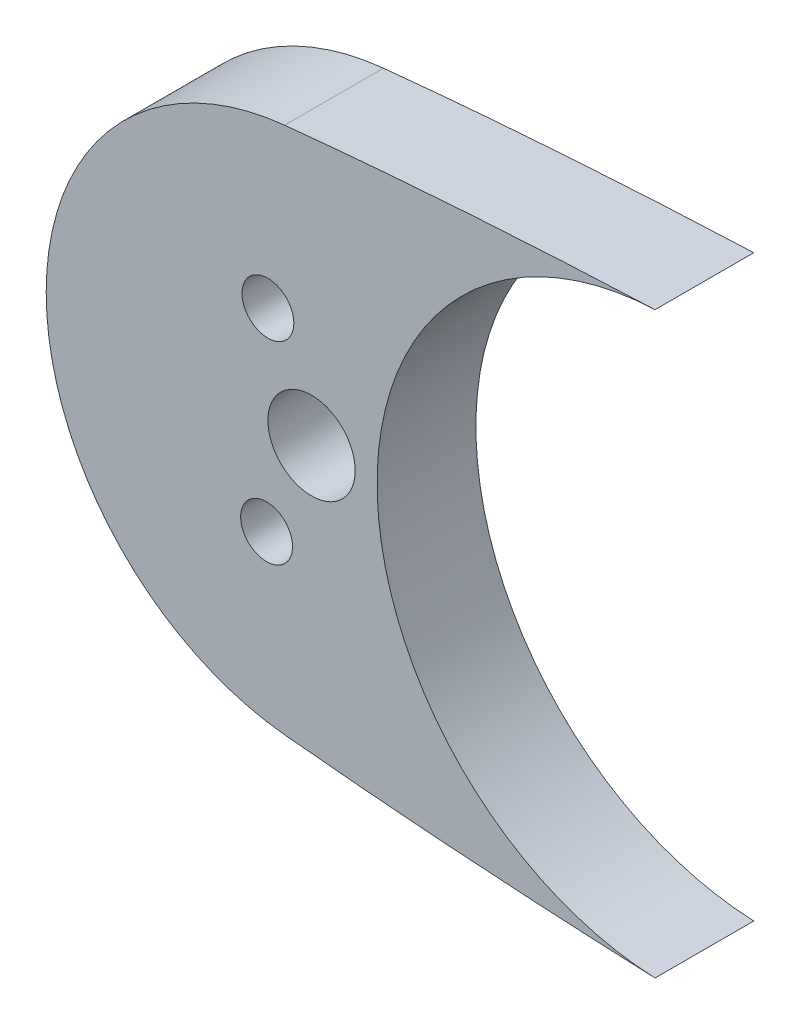
SolidWorks part; units mm, degrees
ref_plane "Front Plane" through (0, 0, 0) normal (0, 0, 1) x (1, 0, 0)
ref_plane "Top Plane" through (0, 0, 0) normal (0, 1, 0) x (1, 0, 0)
ref_plane "Right Plane" through (0, 0, 0) normal (1, 0, 0) x (0, 0, -1)
other "Center of Mass"
curve "Curve2"
  spline degree 3 poles (300, 0.378, 0) (299.8459, 0.3996, 0) (299.2303, 0.4859, 0) (297.8489, 0.6785, 0) (295.556, 0.9968, 0) (292.3657, 1.4334, 0) (288.2979, 1.9834, 0) (283.3772, 2.6357, 0) (277.6343, 3.3815, 0) (271.1045, 4.209, 0) (263.8281, 5.1072, 0) (255.8498, 6.0628, 0) (247.219, 7.0642, 0) (237.9888, 8.0979, 0) (228.216, 9.1511, 0) (217.9611, 10.2107, 0) (207.2872, 11.2632, 0) (196.2601, 12.2937, 0) (184.9478, 13.2887, 0) (173.4201, 14.2316, 0) (161.7479, 15.107, 0) (150.0032, 15.8986, 0) (138.2584, 16.5898, 0) (126.5858, 17.1634, 0) (115.0575, 17.6038, 0) (103.7442, 17.8968, 0) (92.7158, 18.028, 0) (82.0402, 17.9871, 0) (71.7831, 17.7661, 0) (62.0077, 17.3595, 0) (52.7741, 16.7661, 0) (44.1391, 15.9878, 0) (36.1555, 15.0306, 0) (28.872, 13.9026, 0) (22.3327, 12.6157, 0) (16.576, 11.1845, 0) (11.6345, 9.6228, 0) (7.5334, 7.9452, 0) (4.2857, 6.163, 0) (1.8965, 4.2728, 0) (0.3663, 2.2288, 0) (-0.1707, 0, 0) (0.3663, -2.2288, 0) (1.8965, -4.2728, 0) (4.2857, -6.163, 0) (7.5334, -7.9452, 0) (11.6345, -9.6228, 0) (16.576, -11.1845, 0) (22.3327, -12.6157, 0) (28.872, -13.9026, 0) (36.1555, -15.0306, 0) (44.1391, -15.9878, 0) (52.7741, -16.7661, 0) (62.0077, -17.3595, 0) (71.7831, -17.7661, 0) (82.0402, -17.9871, 0) (92.7158, -18.028, 0) (103.7442, -17.8968, 0) (115.0575, -17.6038, 0) (126.5858, -17.1634, 0) (138.2584, -16.5898, 0) (150.0032, -15.8986, 0) (161.7479, -15.107, 0) (173.4201, -14.2316, 0) (184.9478, -13.2887, 0) (196.2601, -12.2937, 0) (207.2872, -11.2632, 0) (217.9611, -10.2107, 0) (228.216, -9.1511, 0) (237.9888, -8.0979, 0) (247.219, -7.0642, 0) (255.8498, -6.0628, 0) (263.8281, -5.1072, 0) (271.1045, -4.209, 0) (277.6343, -3.3815, 0) (283.3772, -2.6357, 0) (288.2979, -1.9834, 0) (292.3657, -1.4334, 0) (295.556, -0.9968, 0) (297.8489, -0.6785, 0) (299.2303, -0.4859, 0) (299.8459, -0.3996, 0) (300, -0.378, 0) knots 0 0 0 0 0.000763 0.003048 0.006841 0.012116 0.018841 0.026973 0.03646 0.047243 0.059254 0.072417 0.086651 0.101866 0.117969 0.134858 0.152428 0.170572 0.189175 0.208122 0.227297 0.24658 0.265853 0.284997 0.303895 0.322433 0.340499 0.357984 0.374788 0.390812 0.405965 0.420162 0.433328 0.445394 0.456301 0.466004 0.474472 0.481696 0.487704 0.492583 0.496544 0.5 0.503456 0.507417 0.512296 0.518304 0.525528 0.533996 0.543699 0.554606 0.566672 0.579838 0.594035 0.609188 0.625212 0.642016 0.659501 0.677567 0.696105 0.715003 0.734147 0.75342 0.772703 0.791878 0.810825 0.829428 0.847572 0.865142 0.882031 0.898134 0.913349 0.927583 0.940746 0.952757 0.96354 0.973027 0.981159 0.987884 0.993159 0.996952 0.999237 1 1 1 1
sketch "Sketch2" plane through (0, 0, 0) normal (0, 0, 1) x (1, 0, 0)
  line L0 (0, 0) -> (300.3287, 0) construction
  line L9 (300, 0.378) -> (300, -0.378)
  line L17 (90, 18.0052) -> (90, -18.0052)
  line L20 (25.2817, 12.903) -> (25.2817, -12.903)
  line L21 (46.6322, 16.1183) -> (46.6322, -16.1183)
  line L22 (68.2099, 17.5933) -> (68.2099, -17.5933)
  line L23 (131.5031, 16.8963) -> (131.5031, -16.8963)
  line L24 (173.2123, 14.1909) -> (173.2123, -14.1909)
  line L25 (215.2898, -10.4186) -> (215.2898, 10.4186)
  line L26 (257.3103, -5.8439) -> (257.3103, 5.8439)
  arc A0 (300, -0.378) -> (300, 0.378) centre (299.947, 0) ccw
  arc A3 (45, 16.0354) -> (45, -16.0354) centre (46.6322, 0) ccw
  arc A5 (67.5, -17.5789) -> (67.5, 17.5789) centre (68.2099, 0) cw
  arc A6 (22.5, 12.5996) -> (22.5, -12.5996) centre (25.2817, 0) ccw
  arc A7 (258, -5.8031) -> (258, 5.8031) centre (257.3103, 0) cw
  arc A8 (216.3287, -10.3667) -> (216.3287, 10.3667) centre (215.2898, 0) cw
  arc A9 (174.3287, -14.147) -> (174.3287, 14.147) centre (173.2123, 0) cw
  arc A11 (132.3287, -16.8761) -> (132.3287, 16.8761) centre (131.5031, 0) cw
  arc A12 (90, -18.0052) -> (90, 18.0052) centre (89.9987, 0) cw
  arc A13 (22.5, 12.5996) -> (22.5, -12.5996) centre (25.2817, 0) cw
  arc A14 (45, 16.0354) -> (45, -16.0354) centre (46.6322, 0) cw
  arc A15 (67.5, 17.5789) -> (67.5, -17.5789) centre (68.2099, 0) cw
  arc A16 (90, -18.0052) -> (90, 18.0052) centre (90, 0) ccw
  arc A17 (132.3287, 16.8761) -> (132.3287, -16.8761) centre (131.5031, 0) cw
  arc A18 (174.3287, 14.147) -> (174.3287, -14.147) centre (173.2123, 0) cw
  arc A19 (216.3287, 10.3667) -> (216.3287, -10.3667) centre (215.2898, 0) cw
  arc A20 (257.9987, 5.8032) -> (257.9987, -5.8032) centre (257.309, 0) cw
  circle A21 centre (25.2817, 0) radius 12.903
  circle A22 centre (257.3103, 0) radius 5.8439
  circle A23 centre (25.2817, 0) radius 2.65
  circle A24 centre (8, 0) radius 2.65
  circle A25 centre (46.6322, 0) radius 2.65
  spline S0 degree 3 poles (1085.0864, 3916.8712) (453.7719, -29.1916) (376.7513, -10.3218) (297.8489, 0.6785) (295.556, 0.9968) (292.3657, 1.4334) (288.2979, 1.9834) (283.3772, 2.6357) (277.6343, 3.3815) (271.1045, 4.209) (263.8281, 5.1072) (255.8498, 6.0628) (247.219, 7.0642) (237.9888, 8.0979) (228.216, 9.1511) (217.9611, 10.2107) (207.2872, 11.2632) (196.2601, 12.2937) (184.9478, 13.2887) (173.4201, 14.2316) (161.7479, 15.107) (150.0032, 15.8986) (138.2584, 16.5898) (126.5858, 17.1634) (115.0575, 17.6038) (103.7442, 17.8968) (92.7158, 18.028) (82.0402, 17.9871) (71.7831, 17.7661) (62.0077, 17.3595) (52.7741, 16.7661) (44.1391, 15.9878) (36.1555, 15.0306) (28.872, 13.9026) (22.3327, 12.6157) (16.576, 11.1845) (11.6345, 9.6228) (7.5334, 7.9452) (4.2857, 6.163) (1.8965, 4.2728) (0.3663, 2.2288) (-0.1707, 0) (0.3663, -2.2288) (1.8965, -4.2728) (4.2857, -6.163) (7.5334, -7.9452) (11.6345, -9.6228) (16.576, -11.1845) (22.3327, -12.6157) (28.872, -13.9026) (36.1555, -15.0306) (44.1391, -15.9878) (52.7741, -16.7661) (62.0077, -17.3595) (71.7831, -17.7661) (82.0402, -17.9871) (92.7158, -18.028) (103.7442, -17.8968) (115.0575, -17.6038) (126.5858, -17.1634) (138.2584, -16.5898) (150.0032, -15.8986) (161.7479, -15.107) (173.4201, -14.2316) (184.9478, -13.2887) (196.2601, -12.2937) (207.2872, -11.2632) (217.9611, -10.2107) (228.216, -9.1511) (237.9888, -8.0979) (247.219, -7.0642) (255.8498, -6.0628) (263.8281, -5.1072) (271.1045, -4.209) (277.6343, -3.3815) (283.3772, -2.6357) (288.2979, -1.9834) (292.3657, -1.4334) (295.556, -0.9968) (297.8489, -0.6785) (376.7507, 10.3217) (453.7706, 29.1913) (1085.0706, -3916.7726) knots -0.383871 -0.383871 -0.383871 -0.383871 0.000763 0.003048 0.006841 0.012116 0.018841 0.026973 0.03646 0.047243 0.059254 0.072417 0.086651 0.101866 0.117969 0.134858 0.152428 0.170572 0.189175 0.208122 0.227297 0.24658 0.265853 0.284997 0.303895 0.322433 0.340499 0.357984 0.374788 0.390812 0.405965 0.420162 0.433328 0.445394 0.456301 0.466004 0.474472 0.481696 0.487704 0.492583 0.496544 0.5 0.503456 0.507417 0.512296 0.518304 0.525528 0.533996 0.543699 0.554606 0.566672 0.579838 0.594035 0.609188 0.625212 0.642016 0.659501 0.677567 0.696105 0.715003 0.734147 0.75342 0.772703 0.791878 0.810825 0.829428 0.847572 0.865142 0.882031 0.898134 0.913349 0.927583 0.940746 0.952757 0.96354 0.973027 0.981159 0.987884 0.993159 0.996952 0.999237 1.383868 1.383868 1.383868 1.383868 only from (300, 0.378) to (300, -0.378) construction
  spline S1 degree 3 poles (300, 0.378) (299.8459, 0.3996) (299.2303, 0.4859) (297.8489, 0.6785) (295.556, 0.9968) (292.3657, 1.4334) (288.2979, 1.9834) (283.3772, 2.6357) (277.6343, 3.3815) (271.1045, 4.209) (263.8281, 5.1072) (255.8498, 6.0628) (247.219, 7.0642) (237.9888, 8.0979) (228.216, 9.1511) (217.9611, 10.2107) (207.2872, 11.2632) (196.2601, 12.2937) (184.9478, 13.2887) (173.4201, 14.2316) (161.7479, 15.107) (150.0032, 15.8986) (138.2584, 16.5898) (126.5858, 17.1634) (115.0575, 17.6038) (103.7442, 17.8968) (92.7158, 18.028) (82.0402, 17.9871) (71.7831, 17.7661) (62.0077, 17.3595) (52.7741, 16.7661) (44.1391, 15.9878) (36.1555, 15.0306) (28.872, 13.9026) (22.3327, 12.6157) (16.576, 11.1845) (11.6345, 9.6228) (7.5334, 7.9452) (4.2857, 6.163) (1.8965, 4.2728) (0.3663, 2.2288) (-0.1707, 0) (0.3663, -2.2288) (1.8965, -4.2728) (4.2857, -6.163) (7.5334, -7.9452) (11.6345, -9.6228) (16.576, -11.1845) (22.3327, -12.6157) (28.872, -13.9026) (36.1555, -15.0306) (44.1391, -15.9878) (52.7741, -16.7661) (62.0077, -17.3595) (71.7831, -17.7661) (82.0402, -17.9871) (92.7158, -18.028) (103.7442, -17.8968) (115.0575, -17.6038) (126.5858, -17.1634) (138.2584, -16.5898) (150.0032, -15.8986) (161.7479, -15.107) (173.4201, -14.2316) (184.9478, -13.2887) (196.2601, -12.2937) (207.2872, -11.2632) (217.9611, -10.2107) (228.216, -9.1511) (237.9888, -8.0979) (247.219, -7.0642) (255.8498, -6.0628) (263.8281, -5.1072) (271.1045, -4.209) (277.6343, -3.3815) (283.3772, -2.6357) (288.2979, -1.9834) (292.3657, -1.4334) (295.556, -0.9968) (297.8489, -0.6785) (299.2303, -0.4859) (299.8459, -0.3996) (300, -0.378) knots 0 0 0 0 0.000763 0.003048 0.006841 0.012116 0.018841 0.026973 0.03646 0.047243 0.059254 0.072417 0.086651 0.101866 0.117969 0.134858 0.152428 0.170572 0.189175 0.208122 0.227297 0.24658 0.265853 0.284997 0.303895 0.322433 0.340499 0.357984 0.374788 0.390812 0.405965 0.420162 0.433328 0.445394 0.456301 0.466004 0.474472 0.481696 0.487704 0.492583 0.496544 0.5 0.503456 0.507417 0.512296 0.518304 0.525528 0.533996 0.543699 0.554606 0.566672 0.579838 0.594035 0.609188 0.625212 0.642016 0.659501 0.677567 0.696105 0.715003 0.734147 0.75342 0.772703 0.791878 0.810825 0.829428 0.847572 0.865142 0.882031 0.898134 0.913349 0.927583 0.940746 0.952757 0.96354 0.973027 0.981159 0.987884 0.993159 0.996952 0.999237 1 1 1 1
  point P47 (215.2898, 0)
  point P58 (257.3103, 0)
  point P61 (12.3787, 0)
  point P62 (62.7505, 0)
  dimension "D11" = 5.3
  dimension "D14" = 5.3
  dimension "D12" = 5.3
  dimension "D1" = 300.3287
  dimension "D2" = 89.9987
  dimension "D3" = 68.2099
  dimension "D4" = 46.6322
  dimension "D5" = 25.2817
  dimension "D6" = 168.8256
  dimension "D7" = 127.1164
  dimension "D8" = 85.0389
  dimension "D9" = 43.0184
  dimension "D10" = 50.3718
  dimension "D13" = 8
extrude "Boss-Extrude3" add sketch "Sketch2" along normal blind 6 from offset 4.25 contours A13 L0 A25 L21 A14 A3 | A3 L0 A13 | L0 A3 A21 | L0 A21 A3 A14 L21 A25 | A25 L0 A5 A14 L21 | L0 A25 L21 A14 A5 | A5 S1 A14 | A14 S1 A5
other "Center of Mass Reference Point1"
sketch "Sketch3" plane through (0, 0, 10.25) normal (0, 0, 1) x (1, 0, 0)
  line L0 (0, 0) -> (65.2465, 0)
  line L1 (43.9027, 0) -> (43.9027, -5.9) construction
  circle A0 centre (43.9027, -5.9) radius 1.575
  circle A1 centre (43.9822, 5.9) radius 1.575
  dimension "D2" = 3.15
  dimension "D4" = 3.15
  dimension "D1" = 5.9
  dimension "D3" = 5.9
extrude "Cut-Extrude1" cut sketch "Sketch3" against normal blind 10
